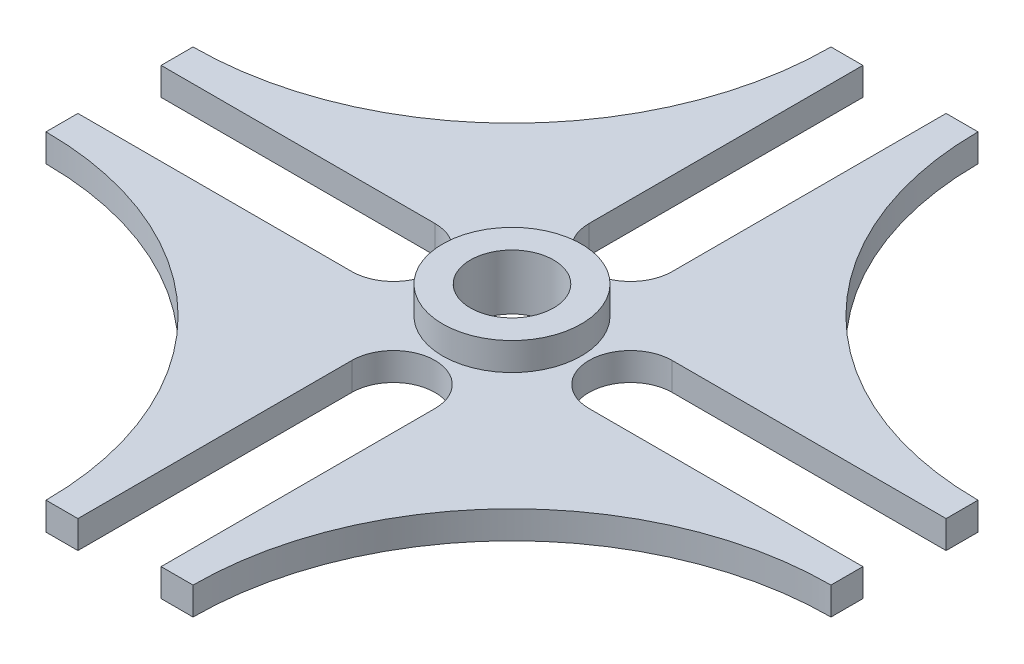
SolidWorks part; units mm, degrees
ref_plane "Front Plane" through (0, 0, 0) normal (0, 0, 1) x (1, 0, 0)
ref_plane "Top Plane" through (0, 0, 0) normal (0, 1, 0) x (1, 0, 0)
ref_plane "Right Plane" through (0, 0, 0) normal (1, 0, 0) x (0, 0, -1)
sketch "Sketch1" plane through (0, 0, 0) normal (0, 1, 0) x (1, 0, 0)
  line L0 (0, 56.6) -> (0, -56.6) construction
  line L1 (-56.6, 0) -> (56.6, 0) construction
  line L2 (6, 56.6) -> (6, 17.1)
  line L3 (17.1, 6) -> (56.6, 6)
  line L4 (6, 56.6) -> (10.6, 56.6)
  line L5 (56.6, 10.6) -> (56.6, 6)
  line L6 (56.6, -6) -> (17.1, -6)
  line L7 (56.6, -6) -> (56.6, -10.6)
  line L8 (6, -17.1) -> (6, -56.6)
  line L9 (10.6, -56.6) -> (6, -56.6)
  line L10 (-6, -56.6) -> (-6, -17.1)
  line L11 (-6, -56.6) -> (-10.6, -56.6)
  line L12 (-17.1, -6) -> (-56.6, -6)
  line L13 (-56.6, -10.6) -> (-56.6, -6)
  line L14 (-56.6, 6) -> (-17.1, 6)
  line L15 (-56.6, 6) -> (-56.6, 10.6)
  line L16 (-6, 17.1) -> (-6, 56.6)
  line L17 (-10.6, 56.6) -> (-6, 56.6)
  arc A0 (10.6, 56.6) -> (56.6, 10.6) centre (56.6, 56.6) ccw
  arc A1 (56.6, -10.6) -> (10.6, -56.6) centre (56.6, -56.6) ccw
  arc A2 (-10.6, -56.6) -> (-56.6, -10.6) centre (-56.6, -56.6) ccw
  arc A3 (-56.6, 10.6) -> (-10.6, 56.6) centre (-56.6, 56.6) ccw
  arc A4 (-6, 17.1) -> (6, 17.1) centre (0, 17.1) ccw
  arc A5 (17.1, 6) -> (17.1, -6) centre (17.1, 0) ccw
  arc A6 (-6, -17.1) -> (6, -17.1) centre (0, -17.1) cw
  arc A7 (-17.1, 6) -> (-17.1, -6) centre (-17.1, 0) cw
  point P4 (0, 0)
  point P8 (0, 0)
  point P38 (0, 0)
  dimension "D4" = 46
  dimension "D6" = 6
  dimension "D1" = 113.2
  dimension "D2" = 6
  dimension "D3" = 6
  dimension "D7" = 39.5
  dimension "D5" = 4
extrude "Boss-Extrude1" add sketch "Sketch1" along normal blind 4
sketch "Sketch2" plane through (0, 4, 0) normal (0, 1, 0) x (1, 0, 0)
  circle A0 centre (0, 0) radius 10
  dimension "D1" = 20
extrude "Boss-Extrude2" add sketch "Sketch2" along normal blind 4
sketch "Sketch3" plane through (0, 8, 0) normal (0, 1, 0) x (1, 0, 0)
  circle A0 centre (0, 0) radius 6
  dimension "D1" = 12
extrude "Cut-Extrude1" cut sketch "Sketch3" against normal through all
equation "\"D3@Sketch1\"=\"D2@Sketch1\""
